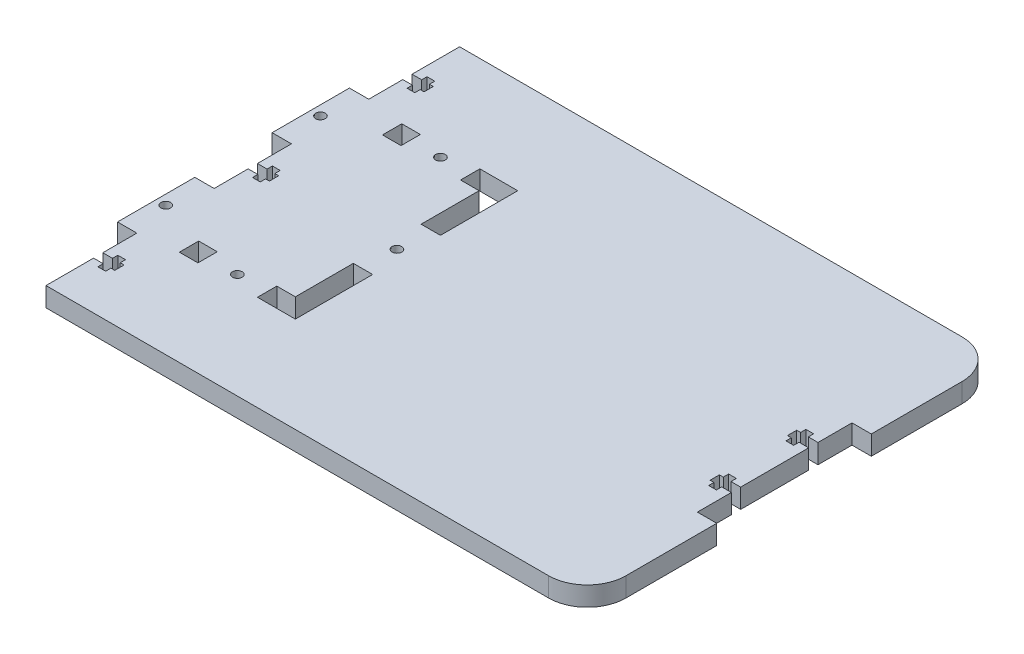
SolidWorks part; units mm, degrees
material "6061 Alloy"
ref_plane "Front Plane" through (0, 0, 0) normal (0, 0, 1) x (1, 0, 0)
ref_plane "Top Plane" through (0, 0, 0) normal (0, 1, 0) x (1, 0, 0)
ref_plane "Right Plane" through (0, 0, 0) normal (1, 0, 0) x (0, 0, -1)
sketch "Sketch1" plane through (0, 0, 0) normal (0, 1, 0) x (1, 0, 0)
  line L0 (-233.986, 84.4709) -> (-68.886, 84.4709)
  line L1 (-233.986, -51.4191) -> (-68.8437, -51.4191)
  line L2 (-233.986, 78.1209) -> (-233.986, 68.8498)
  line L3 (-233.986, 65.802) -> (-233.986, 54.6259)
  line L4 (-233.986, 29.2259) -> (-233.986, 18.0498)
  line L5 (-233.986, 15.002) -> (-233.986, 3.8259)
  line L6 (-233.986, -21.5741) -> (-233.986, -32.7502)
  line L7 (-233.986, -35.798) -> (-233.986, -45.0691)
  line L8 (-227.001, 68.8498) -> (-228.271, 68.8498)
  line L9 (-228.271, 68.8498) -> (-228.271, 70.6024)
  line L10 (-228.271, 70.6024) -> (-230.811, 70.6024)
  line L11 (-230.811, 70.6024) -> (-230.811, 68.8498)
  line L12 (-230.811, 68.8498) -> (-233.986, 68.8498)
  line L13 (-227.001, 65.802) -> (-228.271, 65.802)
  line L14 (-228.271, 65.802) -> (-228.271, 64.0494)
  line L15 (-228.271, 64.0494) -> (-230.811, 64.0494)
  line L16 (-230.811, 64.0494) -> (-230.811, 65.802)
  line L17 (-230.811, 65.802) -> (-233.986, 65.802)
  line L18 (-227.001, 18.0498) -> (-228.271, 18.0498)
  line L19 (-228.271, 18.0498) -> (-228.271, 19.8024)
  line L20 (-228.271, 19.8024) -> (-230.811, 19.8024)
  line L21 (-230.811, 19.8024) -> (-230.811, 18.0498)
  line L22 (-230.811, 18.0498) -> (-233.986, 18.0498)
  line L23 (-227.001, 15.002) -> (-228.271, 15.002)
  line L24 (-228.271, 15.002) -> (-228.271, 13.2494)
  line L25 (-228.271, 13.2494) -> (-230.811, 13.2494)
  line L26 (-230.811, 13.2494) -> (-230.811, 15.002)
  line L27 (-230.811, 15.002) -> (-233.986, 15.002)
  line L28 (-227.001, -32.7502) -> (-228.271, -32.7502)
  line L29 (-228.271, -32.7502) -> (-228.271, -30.9976)
  line L30 (-228.271, -30.9976) -> (-230.811, -30.9976)
  line L31 (-230.811, -30.9976) -> (-230.811, -32.7502)
  line L32 (-230.811, -32.7502) -> (-233.986, -32.7502)
  line L33 (-227.001, -35.798) -> (-228.271, -35.798)
  line L34 (-228.271, -35.798) -> (-228.271, -37.5506)
  line L35 (-228.271, -37.5506) -> (-230.811, -37.5506)
  line L36 (-230.811, -37.5506) -> (-230.811, -35.798)
  line L37 (-230.811, -35.798) -> (-233.986, -35.798)
  line L38 (-233.986, 54.6259) -> (-240.336, 54.6259)
  line L39 (-240.336, 54.6259) -> (-240.336, 29.2259)
  line L40 (-240.336, 29.2259) -> (-233.986, 29.2259)
  line L41 (-233.986, 3.8259) -> (-240.336, 3.8259)
  line L42 (-240.336, 3.8259) -> (-240.336, -21.5741)
  line L43 (-240.336, -21.5741) -> (-233.986, -21.5741)
  line L44 (-233.986, 84.4709) -> (-233.986, 78.1209)
  line L45 (-233.986, -45.0691) -> (-233.986, -51.4191)
  line L46 (-56.186, 71.7709) -> (-56.1746, 41.9259)
  line L47 (-189.821, -20.012) -> (-183.471, -20.012)
  line L48 (-183.471, -20.012) -> (-183.471, 5.388)
  line L49 (-183.471, 5.388) -> (-189.821, 5.388)
  line L50 (-189.821, 5.388) -> (-189.821, -13.662)
  line L51 (-189.821, 53.0638) -> (-183.471, 53.0638)
  line L52 (-183.471, 53.0638) -> (-183.471, 27.6638)
  line L53 (-183.471, 27.6638) -> (-189.821, 27.6638)
  line L54 (-189.821, 27.6638) -> (-189.821, 46.7138)
  line L55 (-62.5148, 16.5259) -> (-62.5148, 27.7019)
  line L56 (-62.5148, 16.5259) -> (-62.5148, 5.3498)
  line L57 (-62.5148, 41.9259) -> (-56.1746, 41.9259)
  line L58 (-62.5148, -8.8741) -> (-56.1551, -8.8741)
  line L59 (-56.1551, -8.8741) -> (-56.1437, -38.7191)
  line L60 (-69.4998, 27.7019) -> (-68.2298, 27.7019)
  line L61 (-68.2298, 27.7019) -> (-68.2298, 25.9493)
  line L62 (-68.2298, 25.9493) -> (-65.6898, 25.9493)
  line L63 (-65.6898, 25.9493) -> (-65.6898, 27.7019)
  line L64 (-65.6898, 27.7019) -> (-62.5148, 27.7019)
  line L65 (-69.4998, 30.7498) -> (-68.2298, 30.7498)
  line L66 (-68.2298, 30.7498) -> (-68.2298, 32.5024)
  line L67 (-68.2298, 32.5024) -> (-65.6898, 32.5024)
  line L68 (-65.6898, 32.5024) -> (-65.6898, 30.7498)
  line L69 (-65.6898, 30.7498) -> (-62.5148, 30.7498)
  line L70 (-69.4998, 2.3019) -> (-68.2298, 2.3019)
  line L71 (-68.2298, 2.3019) -> (-68.2298, 0.5493)
  line L72 (-68.2298, 0.5493) -> (-65.6898, 0.5493)
  line L73 (-65.6898, 0.5493) -> (-65.6898, 2.3019)
  line L74 (-65.6898, 2.3019) -> (-62.5148, 2.3019)
  line L75 (-69.4998, 5.3498) -> (-68.2298, 5.3498)
  line L76 (-68.2298, 5.3498) -> (-68.2298, 7.1024)
  line L77 (-68.2298, 7.1024) -> (-65.6898, 7.1024)
  line L78 (-65.6898, 7.1024) -> (-65.6898, 5.3498)
  line L79 (-65.6898, 5.3498) -> (-62.5148, 5.3498)
  line L80 (-62.5148, 30.7498) -> (-62.5148, 41.9259)
  line L81 (-62.5148, 2.3019) -> (-62.5148, -8.8741)
  line L82 (-221.571, -20.012) -> (-221.571, -13.662)
  line L83 (-221.571, -13.662) -> (-215.475, -13.662)
  line L84 (-215.475, -13.662) -> (-215.475, -20.012)
  line L85 (-215.475, -20.012) -> (-221.571, -20.012)
  line L86 (-195.917, -20.012) -> (-195.917, -13.662)
  line L87 (-195.917, -13.662) -> (-189.821, -13.662)
  line L88 (-189.821, -20.012) -> (-195.917, -20.012)
  line L89 (-221.571, 46.7138) -> (-221.571, 53.0638)
  line L90 (-221.571, 53.0638) -> (-215.475, 53.0638)
  line L91 (-215.475, 53.0638) -> (-215.475, 46.7138)
  line L92 (-215.475, 46.7138) -> (-221.571, 46.7138)
  line L93 (-195.917, 46.7138) -> (-195.917, 53.0638)
  line L94 (-195.917, 53.0638) -> (-189.821, 53.0638)
  line L95 (-189.821, 46.7138) -> (-195.917, 46.7138)
  line L96 (-227.001, 68.8498) -> (-227.001, 65.802)
  line L97 (-227.001, 18.0498) -> (-227.001, 15.002)
  line L98 (-227.001, -32.7502) -> (-227.001, -35.798)
  line L99 (-69.4998, 30.7498) -> (-69.4998, 27.7019)
  line L100 (-69.4998, 5.3498) -> (-69.4998, 2.3019)
  circle A0 centre (-237.161, 41.9259) radius 1.5875
  circle A1 centre (-237.161, -8.8741) radius 1.5875
  arc A2 (-56.186, 71.7709) -> (-68.886, 84.4709) centre (-68.886, 71.7709) ccw
  arc A3 (-68.8437, -51.4191) -> (-56.1437, -38.7191) centre (-68.8437, -38.7191) ccw
  circle A4 centre (-186.646, 16.5425) radius 1.5875
  circle A5 centre (-205.696, -16.837) radius 1.5875
  circle A6 centre (-205.696, 49.8888) radius 1.5875
extrude "Boss-Extrude1" add sketch "Sketch1" along normal blind 6.35
